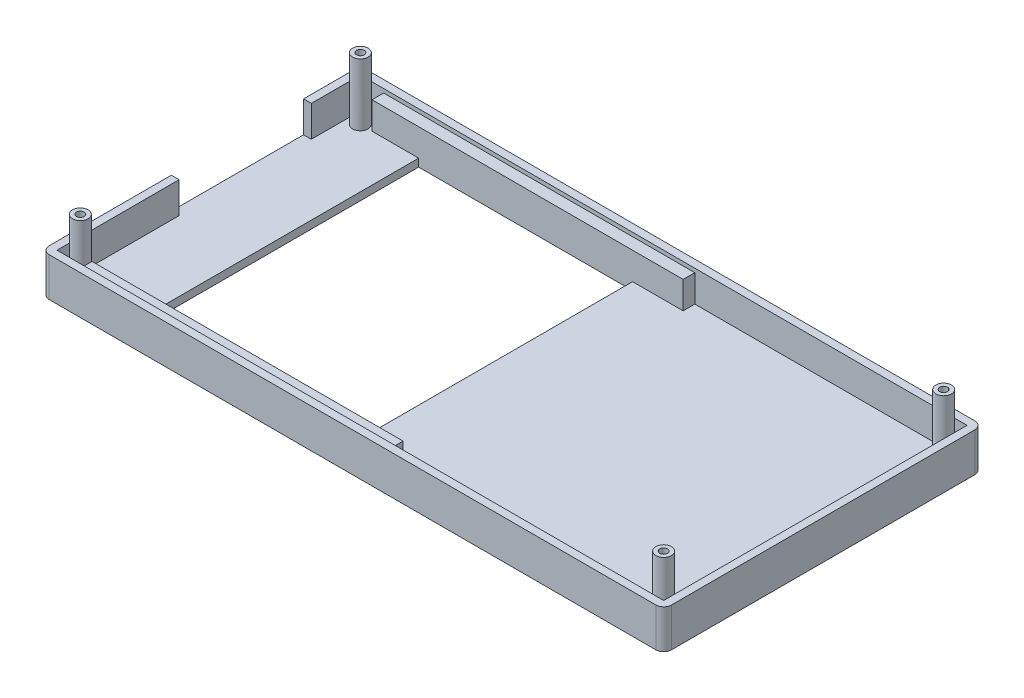
SolidWorks part; units mm, degrees
ref_plane "Front Plane" through (0, 0, 0) normal (0, 0, 1) x (1, 0, 0)
ref_plane "Top Plane" through (0, 0, 0) normal (0, 1, 0) x (1, 0, 0)
ref_plane "Right Plane" through (0, 0, 0) normal (1, 0, 0) x (0, 0, -1)
sketch "Sketch1" plane through (0, 0, 0) normal (0, 1, 0) x (1, 0, 0)
  line L1 (-80, -41) -> (80, -41)
  line L2 (-80, -41) -> (-80, 41)
  line L3 (-80, 41) -> (80, 41)
  line L4 (80, -41) -> (80, 41)
  line L5 (-80, -41) -> (80, 41) construction
  line L6 (-80, 41) -> (80, -41) construction
  point P0 (0, 0)
  dimension "D1" = 160
  dimension "D2" = 82
extrude "Boss-Extrude1" add sketch "Sketch1" along normal blind 10 contours L1 L4 L3 L2
shell "Shell1" thickness 2
sketch "Sketch2" plane through (0, 2, 0) normal (0, 1, 0) x (1, 0, 0)
  line L0 (-78, 39) -> (78, 39) construction
  line L1 (-78, -39) -> (-78, 39) construction
  line L2 (0, 39) -> (0, -41) construction
  line L3 (-78, 39) -> (78, 39) construction
  line L4 (-80, -41) -> (80, -41) construction
  line L5 (-80, 0) -> (80, 0) construction
  line L6 (-80, -41) -> (-80, 41) construction
  line L7 (80, -41) -> (80, 41) construction
  circle A0 centre (-75, 36) radius 1
  circle A1 centre (75, 36) radius 1
  circle A2 centre (75, -36) radius 1
  circle A3 centre (-75, -36) radius 1
  circle A4 centre (-75, 36) radius 2
  circle A5 centre (75, 36) radius 2
  circle A6 centre (-75, -36) radius 2
  circle A7 centre (75, -36) radius 2
  dimension "D1" = 3
  dimension "D2" = 3
  dimension "D3" = 2
  dimension "D4" = 1
fillet "Fillet1" radius 2 1 edges at (-80, 5, 41)
fillet "Fillet2" radius 2 1 edges at (-80, 5, -41)
fillet "Fillet3" radius 2 1 edges at (80, 5, -41)
fillet "Fillet4" radius 2 1 edges at (80, 5, 41)
sketch "Sketch10" plane through (-80, 0, 0) normal (-1, 0, 0) x (0, 0, 1)
  line L0 (7.6, 0) -> (-26.4, 0)
  line L1 (-41, 0) -> (-41, 10) construction
  line L2 (39, 0) -> (-39, 0) construction
  line L3 (-26.4, 0) -> (-26.4, 2)
  line L4 (-26.4, 2) -> (7.6, 2)
  line L5 (-26.4, 2) -> (7.6, 2)
  line L6 (-26.4, 2) -> (-26.4, 10.0297)
  line L7 (7.6, 2) -> (7.6, 10.0297)
  line L8 (-26.4, 10.0297) -> (7.6, 10.0297)
  dimension "D1" = 34
  dimension "D2" = 14.6
  dimension "D3" = 2
extrude "Cut-Extrude1" cut sketch "Sketch10" against normal blind 6 contours L4 L7 L8 L6
extrude "Boss-Extrude7" add sketch "Sketch2" along normal blind 16 contours A0 | A3 | A6 | A2 | A7 | A5 | A1 | A4
sketch "Sketch12" plane through (0, 2, 0) normal (0, 1, 0) x (1, 0, 0)
  line L0 (-55.169, 27.9209) -> (-55.169, 31.6209)
  line L1 (-55.169, -20.9591) -> (-55.169, -24.6591)
  line L2 (2.731, -20.9591) -> (2.731, -24.6591)
  line L3 (2.731, 27.9209) -> (2.731, 31.6209)
  line L4 (-78, -39) -> (-78, -7.6) construction
  line L5 (-72, 39) -> (8, 39)
  line L6 (-72, 39) -> (-72, 36)
  line L7 (-72, 36) -> (8, 36)
  line L8 (8, 39) -> (8, 36)
  line L9 (71.831, 0) -> (-89.6429, 0) construction
  line L11 (8, -39) -> (8, -36)
  line L12 (-72, -39) -> (8, -39)
  line L13 (-72, -39) -> (-72, -36)
  line L14 (-72, -36) -> (8, -36)
  line L15 (-78, -39) -> (78, -39) construction
  line L16 (-78, 39) -> (78, 39) construction
  dimension "D1" = 3.7
  dimension "D2" = 3.7
  dimension "D3" = 3
  dimension "D4" = 80
  dimension "D5" = 0
  dimension "D6" = 0
  dimension "D7" = 6
extrude "Boss-Extrude8" add sketch "Sketch12" along normal blind 7 contours L6 L7 L8 L5 | L14 L11 L12 L13
sketch "Sketch13" plane through (0, 2, 0) normal (0, 1, 0) x (1, 0, 0)
  line L1 (-60, 36) -> (-5, 36)
  line L2 (-60, 36) -> (-60, -36)
  line L3 (-60, -36) -> (-5, -36)
  line L4 (-5, 36) -> (-5, -36)
  line L5 (-78, -39) -> (78, -39) construction
  line L6 (-78, 26.4) -> (-78, 39) construction
  dimension "D1" = 72
  dimension "D2" = 3
  dimension "D3" = 55
  dimension "D4" = 18
extrude "Cut-Extrude3" cut sketch "Sketch13" against normal blind 200 contours L1 L4 L3 L2
